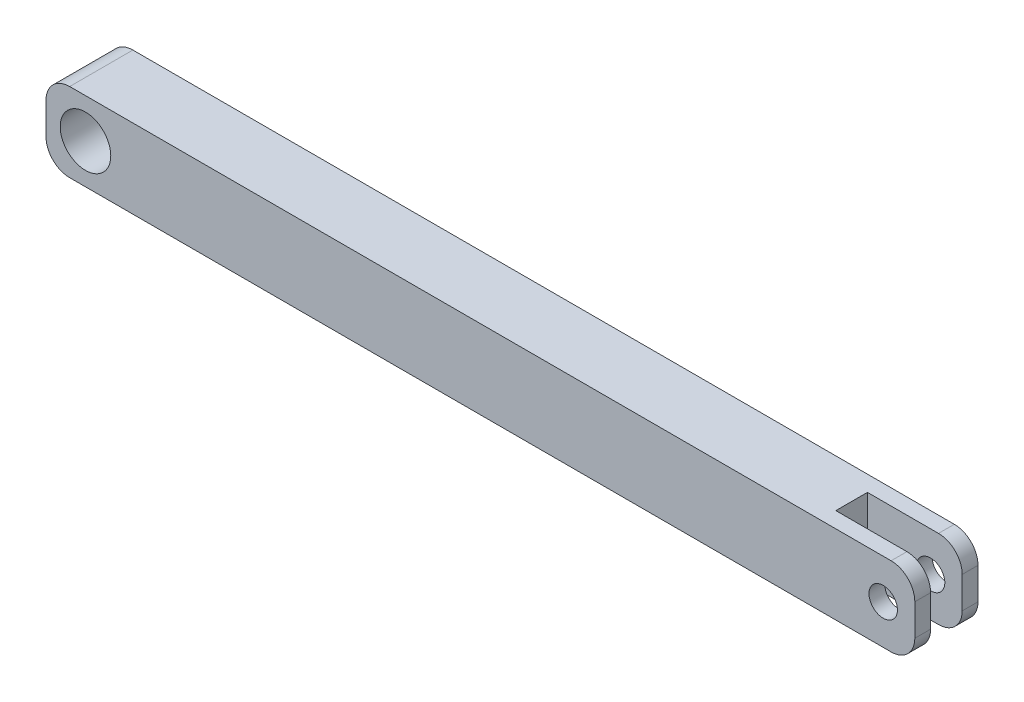
SolidWorks part; units mm, degrees
ref_plane "前视基准面" through (0, 0, 0) normal (0, 0, 1) x (1, 0, 0)
ref_plane "上视基准面" through (0, 0, 0) normal (0, 1, 0) x (1, 0, 0)
ref_plane "右视基准面" through (0, 0, 0) normal (1, 0, 0) x (0, 0, -1)
other "Configuration Table"
sketch "草图5" plane through (0, 0, 0) normal (0, 1, 0) x (1, 0, 0)
  line L0 (0, 0) -> (0, -3)
  line L4 (55, -3) -> (55, 0)
  line L8 (55, 0) -> (0, 0)
  line L9 (0, -3) -> (55, -3)
  dimension "D6" = 3
  dimension "D1" = 55
  dimension "D5" = 3
extrude "凸台-拉伸1" add sketch "草图5" along normal blind 5
sketch "草图6" plane through (0, 0, 3) normal (0, 0, 1) x (1, 0, 0)
  line L2 (0, 5) -> (0, 0) construction
  line L3 (0, 5) -> (55, 5) construction
  circle A0 centre (2.5, 2.5) radius 1.6
  dimension "D1" = 3.2
  dimension "D2" = 2.5
  dimension "D3" = 2.5
extrude "切除-拉伸1" cut sketch "草图6" against normal up to next
sketch "草图7" plane through (0, 0, 0) normal (0, 0, 1) x (1, 0, 0)
  line L0 (55, 5) -> (55, 0) construction
  circle A0 centre (53, 2.5) radius 0.9
  point P6 (55, 2.5)
  dimension "D1" = 1.8
  dimension "D2" = 2
extrude "切除-拉伸2" cut sketch "草图7" along normal up to next
fillet "圆角1" radius 1.5 4 edges at (55, 5, 1.5) (55, 0, 1.5) (0, 0, 1.5) (0, 5, 1.5)
sketch "草图8" plane through (0, 5, 0) normal (0, 1, 0) x (1, 0, 0)
  line L0 (55, 0) -> (55, -3) construction
  line L1 (55, -0.7) -> (49, -0.7)
  line L2 (55, -0.7) -> (55, -2.3)
  line L3 (55, -2.3) -> (49, -2.3)
  line L4 (49, -0.7) -> (49, -2.3)
  point P6 (55, -1.5)
  dimension "D1" = 1.6
  dimension "D2" = 6
extrude "切除-拉伸3" cut sketch "草图8" against normal blind 10
sketch "草图10" plane through (0, 0, 3) normal (0, 0, 1) x (1, 0, 0)
  line L4 (55, 1.5) -> (55, 3.5)
  line L5 (53.5, 5) -> (1.5, 5)
  line L6 (0, 3.5) -> (0, 1.5)
  line L7 (1.5, 0) -> (53.5, 0)
  line L8 (55, 1.5) -> (55, 3.5)
  line L9 (53.5, 5) -> (1.5, 5)
  line L10 (0, 3.5) -> (0, 1.5)
  line L11 (1.5, 0) -> (53.5, 0)
  circle A0 centre (2.5, 2.5) radius 1.6 construction
  circle A1 centre (2.5, 2.5) radius 1.6
  circle A2 centre (53, 2.5) radius 0.9 construction
  circle A3 centre (53, 2.5) radius 0.9
  arc A4 (55, 3.5) -> (53.5, 5) centre (53.5, 3.5) ccw
  arc A5 (1.5, 5) -> (0, 3.5) centre (1.5, 3.5) ccw
  arc A6 (0, 1.5) -> (1.5, 0) centre (1.5, 1.5) ccw
  arc A7 (53.5, 0) -> (55, 1.5) centre (53.5, 1.5) ccw
  arc A8 (55, 3.5) -> (53.5, 5) centre (53.5, 3.5) ccw
  arc A9 (1.5, 5) -> (0, 3.5) centre (1.5, 3.5) ccw
  arc A10 (0, 1.5) -> (1.5, 0) centre (1.5, 1.5) ccw
  arc A11 (53.5, 0) -> (55, 1.5) centre (53.5, 1.5) ccw
  dimension "D1" = 0
extrude "凸台-拉伸2" add sketch "草图10" along normal blind 0.5
sketch "草图11" plane through (0, 0, 0) normal (0, 0, -1) x (-1, 0, 0)
  line L4 (-1.5, 5) -> (-53.5, 5)
  line L5 (-55, 3.5) -> (-55, 1.5)
  line L6 (-53.5, 0) -> (-1.5, 0)
  line L7 (0, 1.5) -> (0, 3.5)
  line L8 (-1.5, 5) -> (-53.5, 5)
  line L9 (-55, 3.5) -> (-55, 1.5)
  line L10 (-53.5, 0) -> (-1.5, 0)
  line L11 (0, 1.5) -> (0, 3.5)
  circle A0 centre (-53, 2.5) radius 0.9 construction
  circle A1 centre (-2.5, 2.5) radius 1.6 construction
  circle A2 centre (-53, 2.5) radius 0.9
  circle A3 centre (-2.5, 2.5) radius 1.6
  arc A4 (-53.5, 5) -> (-55, 3.5) centre (-53.5, 3.5) ccw
  arc A5 (-55, 1.5) -> (-53.5, 0) centre (-53.5, 1.5) ccw
  arc A6 (-1.5, 0) -> (0, 1.5) centre (-1.5, 1.5) ccw
  arc A7 (0, 3.5) -> (-1.5, 5) centre (-1.5, 3.5) ccw
  arc A8 (-53.5, 5) -> (-55, 3.5) centre (-53.5, 3.5) ccw
  arc A9 (-55, 1.5) -> (-53.5, 0) centre (-53.5, 1.5) ccw
  arc A10 (-1.5, 0) -> (0, 1.5) centre (-1.5, 1.5) ccw
  arc A11 (0, 3.5) -> (-1.5, 5) centre (-1.5, 3.5) ccw
  dimension "D1" = 0
extrude "凸台-拉伸3" add sketch "草图11" along normal blind 0.5
sketch "草图12" plane through (0, 0, 0) normal (0, -1, 0) x (1, 0, 0)
  line L0 (49, 2.3) -> (53.5, 2.3) construction
  line L1 (55.0706, 0.5) -> (49, 0.5)
  line L2 (55.0706, 0.5) -> (55.0706, 2.5)
  line L3 (55.0706, 2.5) -> (49, 2.5)
  line L4 (49, 0.5) -> (49, 2.5)
  line L5 (55.0706, 0.5) -> (49, 2.5) construction
  line L6 (55.0706, 2.5) -> (49, 0.5) construction
  line L7 (53.5, 0.7) -> (49, 0.7) construction
  point P0 (52.0353, 1.5)
  dimension "D1" = 0.2
  dimension "D2" = 0.2
extrude "切除-拉伸4" cut sketch "草图12" against normal blind 10
